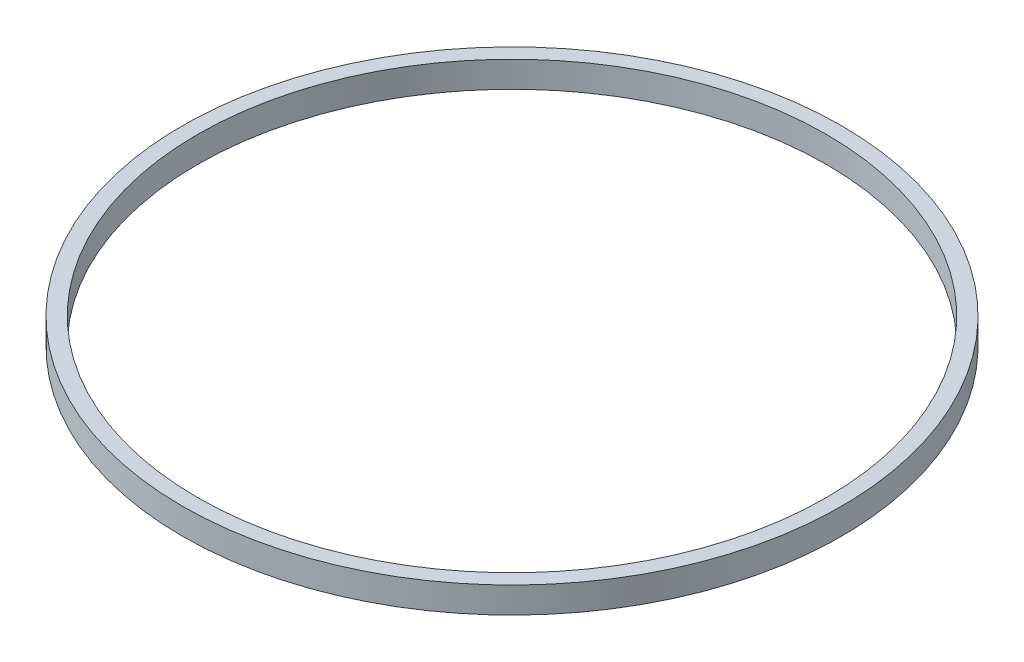
SolidWorks part; units mm, degrees
material "Pine"
ref_plane "Front Plane" through (0, 0, 0) normal (0, 0, 1) x (1, 0, 0)
ref_plane "Top Plane" through (0, 0, 0) normal (0, 1, 0) x (1, 0, 0)
ref_plane "Right Plane" through (0, 0, 0) normal (1, 0, 0) x (0, 0, -1)
sketch "Sketch1" plane through (0, 0, 0) normal (0, 1, 0) x (1, 0, 0)
  circle A0 centre (0, 0) radius 240.5
  circle A1 centre (0, 0) radius 229.5
  dimension "D1" = 481
  dimension "D2" = 459
extrude "Boss-Extrude1" add sketch "Sketch1" along normal mid plane 19
